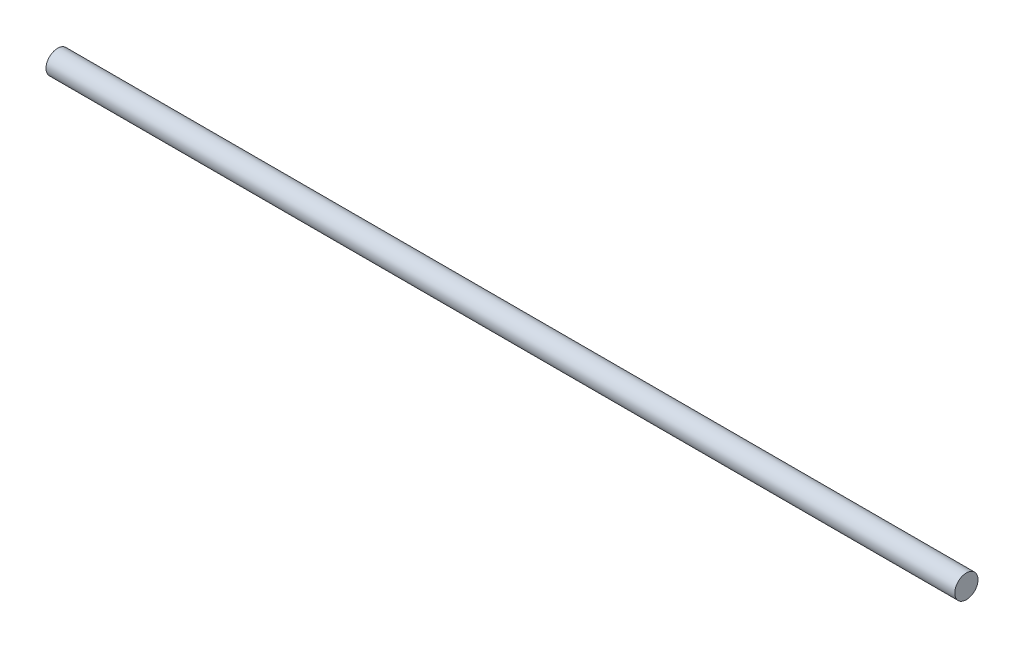
SolidWorks part; units mm, degrees
material "Hexcel AS4C (3000 Filaments)"
ref_plane "Front Plane" through (0, 0, 0) normal (0, 0, 1) x (1, 0, 0)
ref_plane "Top Plane" through (0, 0, 0) normal (0, 1, 0) x (1, 0, 0)
ref_plane "Right Plane" through (0, 0, 0) normal (1, 0, 0) x (0, 0, -1)
sketch "Sketch1" plane through (0, 0, 0) normal (1, 0, 0) x (0, 0, -1)
  circle A0 centre (0, 0) radius 1.016
  dimension "D1" = 2.032
extrude "Boss-Extrude1" add sketch "Sketch1" along normal blind 79.375
